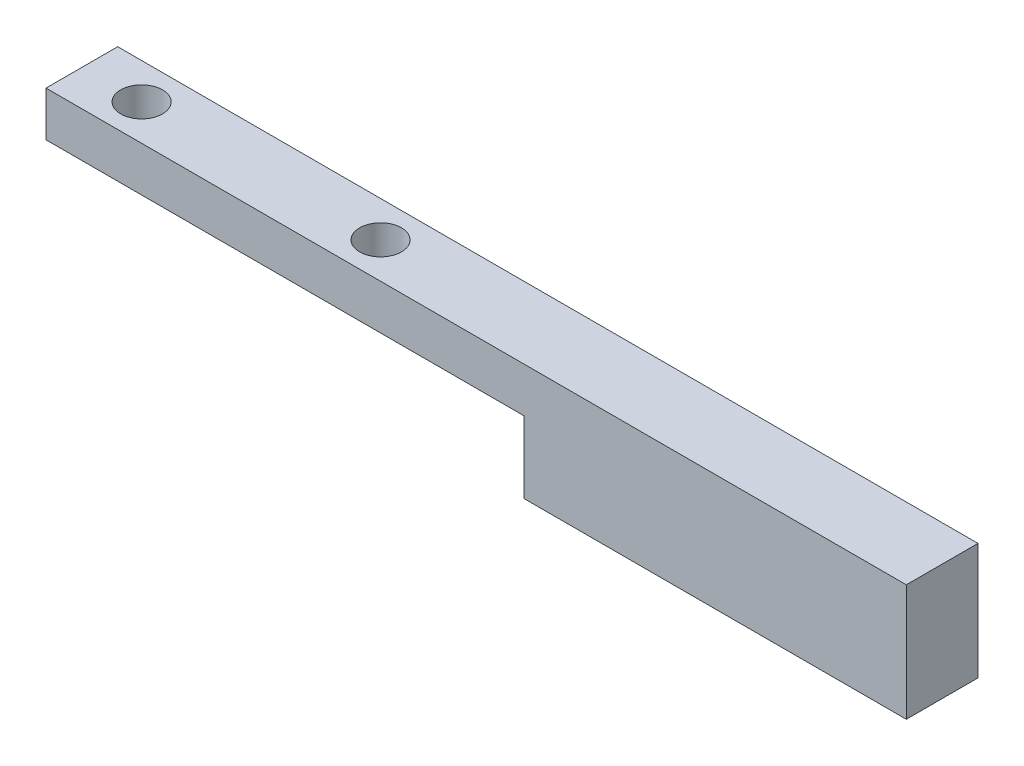
SolidWorks part; units mm, degrees
material "ABS"
ref_plane "前视基准面" through (0, 0, 0) normal (0, 0, 1) x (1, 0, 0)
ref_plane "上视基准面" through (0, 0, 0) normal (0, 1, 0) x (1, 0, 0)
ref_plane "右视基准面" through (0, 0, 0) normal (1, 0, 0) x (0, 0, -1)
other "Configuration Table"
sketch "草图1" plane through (0, 0, 0) normal (0, 1, 0) x (1, 0, 0)
  line L1 (-20, 3) -> (20, 3)
  line L2 (-20, 3) -> (-20, -3)
  line L3 (-20, -3) -> (20, -3)
  line L4 (20, 3) -> (20, -3)
  line L5 (-20, 3) -> (20, -3) construction
  line L6 (-20, -3) -> (20, 3) construction
  circle A0 centre (-15, 0) radius 1.75
  circle A1 centre (5, 0) radius 1.75
  point P0 (0, 0)
  dimension "D5" = 3.5
  dimension "D1" = 40
  dimension "D2" = 6
  dimension "D3" = 20
  dimension "D4" = 5
extrude "凸台-拉伸1" add sketch "草图1" along normal blind 3.75
sketch "草图2" plane through (20, 0, 0) normal (1, 0, 0) x (0, 0, -1)
  line L1 (-3, -6) -> (3, -6)
  line L2 (-3, -6) -> (-3, 3.75)
  line L3 (-3, 3.75) -> (3, 3.75)
  line L4 (3, -6) -> (3, 3.75)
  line L5 (-3, 3.75) -> (-3, 0) construction
  line L6 (-17.7661, -6) -> (2, -6) construction
  point P6 (-2.7, -4.6807)
  point P7 (-3, 3.75)
  point P9 (3, 3.75)
  point P11 (-2.7, -4.6035)
  point P12 (-2.7, -4.8701)
  point P13 (-2.7, 3.75)
  point P14 (0, 0)
  point P16 (-3, -4.8559)
  point P17 (-3, -6)
extrude "凸台-拉伸2" add sketch "草图2" along normal blind 32
